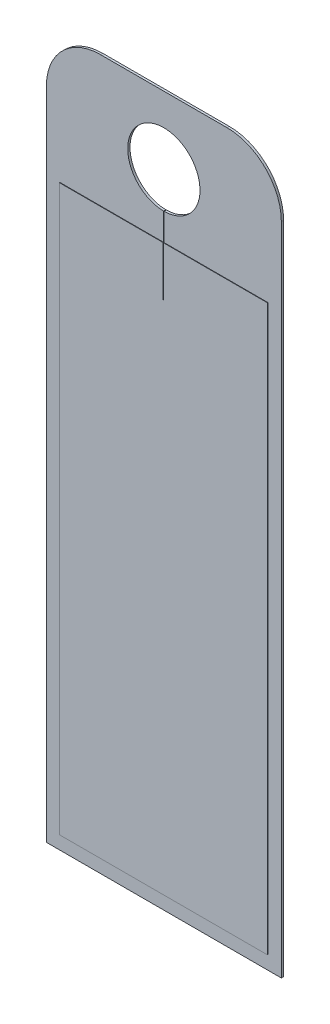
SolidWorks part; units mm, degrees
ref_plane "Front Plane" through (0, 0, 0) normal (0, 0, 1) x (1, 0, 0)
ref_plane "Top Plane" through (0, 0, 0) normal (0, 1, 0) x (1, 0, 0)
ref_plane "Right Plane" through (0, 0, 0) normal (1, 0, 0) x (0, 0, -1)
sketch "Sketch2" plane through (0, 0, 0) normal (0, 0, 1) x (1, 0, 0)
  line L0 (0, 0) -> (0, -142) construction
  line L1 (-14, 15) -> (14, 15)
  line L2 (-26, 3) -> (-26, -142)
  line L3 (-26, -142) -> (26, -142)
  line L4 (26, 3) -> (26, -142)
  circle A0 centre (0, 0) radius 8
  arc A1 (-14, 15) -> (-26, 3) centre (-14, 3) ccw
  arc A2 (14, 15) -> (26, 3) centre (14, 3) cw
  point P11 (-26, 15)
  point P14 (26, 15)
  dimension "D1" = 16
  dimension "D2" = 12
  dimension "D3" = 15
  dimension "D4" = 52
  dimension "D6" = 157
extrude "Boss-Extrude1" add sketch "Sketch2" along normal blind 0.5
sketch "Sketch4" plane through (0, 0, 0.5) normal (0, 0, 1) x (1, 0, 0)
  line L0 (0, 0) -> (0, -161.7324) construction
  line L1 (-23, -14) -> (23, -14)
  line L2 (-23, -14) -> (-23, -139)
  line L3 (-23, -139) -> (23, -139)
  line L4 (23, -14) -> (23, -139)
  line L5 (-26, -142) -> (26, -142) construction
  dimension "D1" = 46
  dimension "D2" = 3
  dimension "D3" = 125
extrude "Boss-Extrude2" add sketch "Sketch4" along normal blind 0.1 and the other way offset from surface (0.6 mm away) 0.1 other way up to face at (0, -40.5049, 0)
sketch "Sketch5" plane through (0, 0, 0.5) normal (0, 0, 1) x (1, 0, 0)
  line L0 (0, 0) -> (0, -37.9495) construction
  line L6 (-0.05, 0) -> (0.05, 0)
  line L7 (-0.05, 0) -> (-0.05, -25)
  line L8 (-0.05, -25) -> (0.05, -25)
  line L9 (0.05, 0) -> (0.05, -25)
  point P7 (0, 0)
  dimension "D1" = 25
  dimension "D2" = 0.1
extrude "Cut-Extrude1" cut sketch "Sketch5" against normal through all and the other way through all
